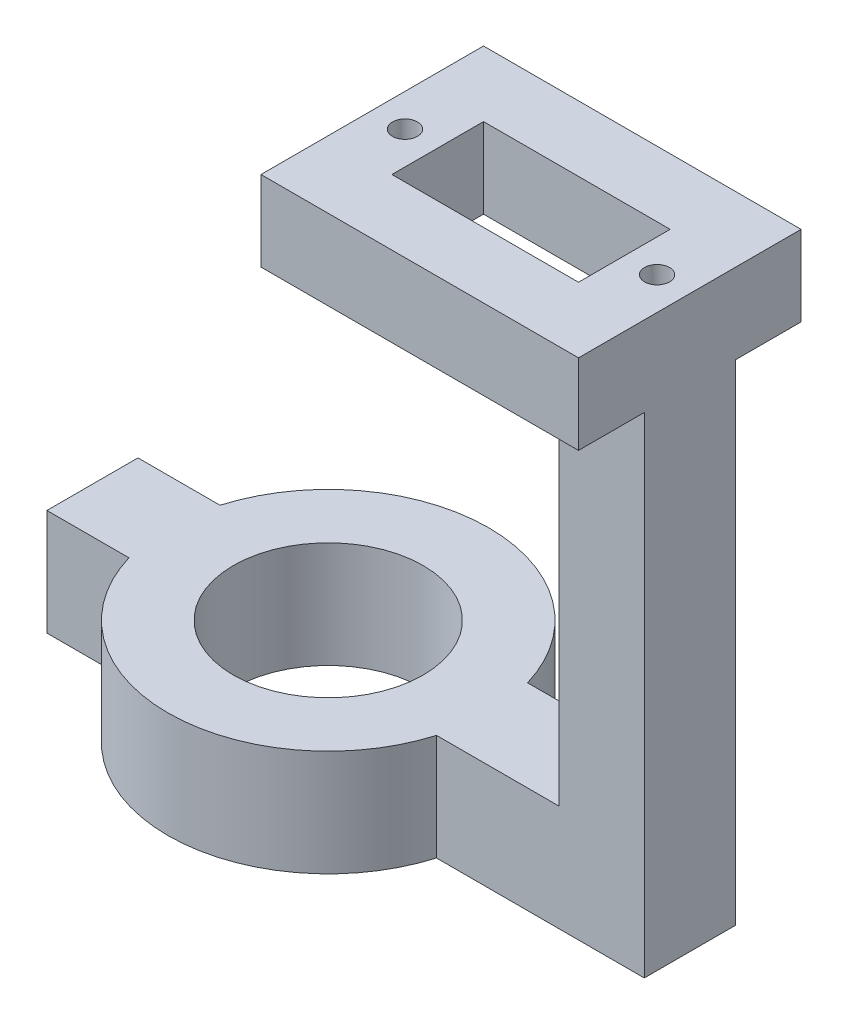
SolidWorks part; units mm, degrees
ref_plane "前基準面" through (0, 0, 0) normal (0, 0, 1) x (1, 0, 0)
ref_plane "上基準面" through (0, 0, 0) normal (0, 1, 0) x (1, 0, 0)
ref_plane "右基準面" through (0, 0, 0) normal (1, 0, 0) x (0, 0, -1)
sketch "草圖1" plane through (0, 0, 0) normal (0, 1, 0) x (1, 0, 0)
  line L1 (-14.255, 7) -> (14.255, 7)
  line L2 (-14.255, 7) -> (-14.255, -7)
  line L3 (-14.255, -7) -> (14.255, -7)
  line L4 (14.255, 7) -> (14.255, -7)
  line L5 (-14.255, 7) -> (14.255, -7) construction
  line L6 (-14.255, -7) -> (14.255, 7) construction
  point P0 (0, 0)
  dimension "D1" = 14
  dimension "D2" = 28.51
extrude "伸長-薄件1" add sketch "草圖1" along normal blind 12.25 thin thin type one direction wall 10
sketch "草圖2" plane through (0, 12.25, 0) normal (0, 1, 0) x (1, 0, 0)
  line L0 (-1014.255, 0) -> (48985.745, 0) construction
  line L1 (-14.255, 7) -> (-14.255, -7) construction
  line L2 (-19.255, -988.4004) -> (-19.255, 49011.5996) construction
  line L3 (-24.255, 17) -> (-19.255, 17) construction
  line L4 (-24.255, 17) -> (-24.255, 11.5996) construction
  line L5 (-24.255, 11.5996) -> (-19.255, 11.5996) construction
  line L6 (-19.255, 17) -> (-19.255, 11.5996) construction
  line L7 (24.255, 17) -> (19.255, 17) construction
  line L8 (24.255, 17) -> (24.255, 12.4477) construction
  line L9 (24.255, 12.4477) -> (19.255, 12.4477) construction
  line L10 (19.255, 17) -> (19.255, 12.4477) construction
  line L11 (19.255, -987.5523) -> (19.255, 49012.4477) construction
  circle A0 centre (-19.255, 0) radius 1.91
  circle A1 centre (19.255, 0) radius 1.91
  point P5 (-14.255, 0)
  dimension "D3" = 3.82
  dimension "D4" = 3.82
  dimension "D1" = 5
  dimension "D2" = 5
extrude "除料-伸長1" cut sketch "草圖2" against normal through all
sketch "草圖4" plane through (0, 0, 0) normal (0, -1, 0) x (1, 0, 0)
  line L0 (-1000, 0) -> (49000, 0) construction
  line L1 (24.255, 17) -> (24.255, -17) construction
  line L2 (11.255, 6.955) -> (24.255, 6.955)
  line L3 (11.255, 6.955) -> (11.255, -6.955)
  line L4 (11.255, -6.955) -> (24.255, -6.955)
  line L5 (24.255, 6.955) -> (24.255, -6.955)
  line L6 (11.255, 6.955) -> (24.255, -6.955) construction
  line L7 (11.255, -6.955) -> (24.255, 6.955) construction
  point P1 (17.755, 0)
  dimension "D1" = 13.91
  dimension "D2" = 13
extrude "填料-伸長1" add sketch "草圖4" along normal blind 74.82
sketch "草圖5" plane through (11.255, 0, 0) normal (-1, 0, 0) x (0, 0, 1)
  line L0 (6.955, -74.82) -> (6.955, 0) construction
  line L1 (-6.955, -74.82) -> (6.955, -74.82)
  line L2 (-6.955, -74.82) -> (-6.955, -58.59)
  line L3 (-6.955, -58.59) -> (6.955, -58.59)
  line L4 (6.955, -74.82) -> (6.955, -58.59)
  dimension "D1" = 16.23
extrude "填料-伸長2" add sketch "草圖5" along normal blind 23.57
sketch "草圖7" plane through (0, -74.82, 0) normal (0, -1, 0) x (1, 0, 0)
  circle A0 centre (-30.9782, 0) radius 14.5
  dimension "D1" = 29
extrude "伸長-薄件2" add sketch "草圖7" against normal blind 16.23 thin
ref_plane "平面1" through (-60, 0, 0) normal (1, 0, 0) x (0, 0, -1)
sketch "草圖9" plane through (-60, 0, 0) normal (1, 0, 0) x (0, 0, -1)
  line L1 (6.955, -58.59) -> (-6.955, -58.59)
  line L2 (6.955, -58.59) -> (6.955, -74.82)
  line L3 (6.955, -74.82) -> (-6.955, -74.82)
  line L4 (-6.955, -58.59) -> (-6.955, -74.82)
extrude "填料-伸長3" add sketch "草圖9" along normal blind 13.15 and the other way blind 7
